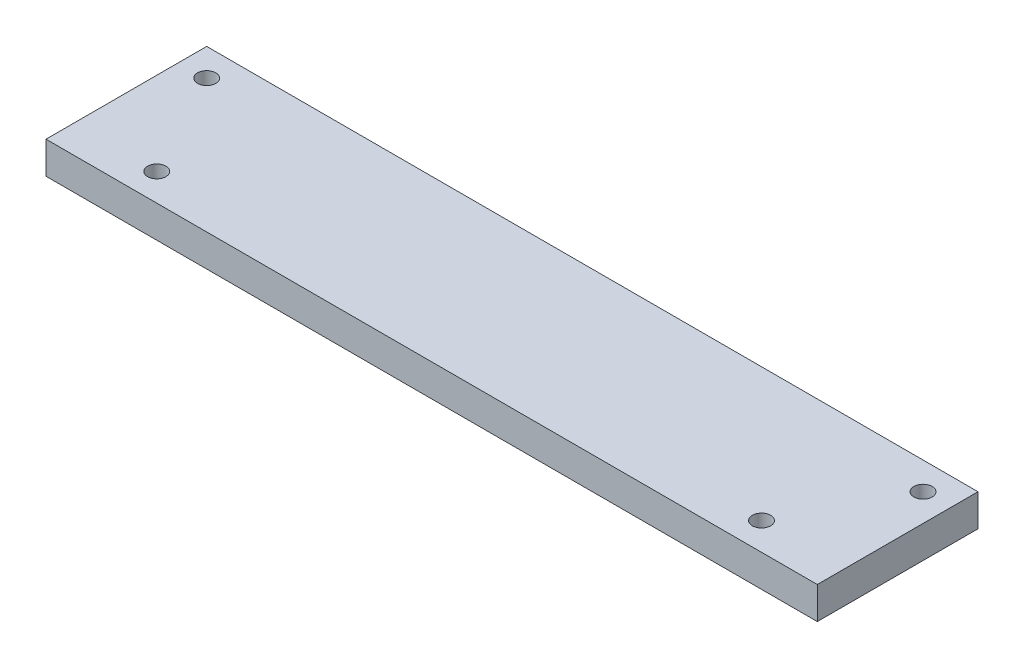
SolidWorks part; units mm, degrees
material "Pine"
ref_plane "Front Plane" through (0, 0, 0) normal (0, 0, 1) x (1, 0, 0)
ref_plane "Top Plane" through (0, 0, 0) normal (0, 1, 0) x (1, 0, 0)
ref_plane "Right Plane" through (0, 0, 0) normal (1, 0, 0) x (0, 0, -1)
sketch "Sketch2" plane through (0, 0, 0) normal (0, 1, 0) x (1, 0, 0)
  line L0 (293.9415, 52.6415) -> (271.8921, 10.8585) construction
  line L1 (0, 0) -> (304.8, 0)
  line L2 (0, 0) -> (0, 63.5)
  line L3 (0, 63.5) -> (304.8, 63.5)
  line L4 (304.8, 0) -> (304.8, 63.5)
  line L5 (152.4, 63.5) -> (152.4, -83.5762) construction
  circle A0 centre (293.9415, 52.6415) radius 3.6195
  circle A1 centre (271.8921, 10.8585) radius 3.6195
  circle A2 centre (32.9079, 10.8585) radius 3.6195
  circle A3 centre (10.8585, 52.6415) radius 3.6195
  point P11 (152.4, 63.5)
  dimension "D3" = 7.239
  dimension "D1" = 304.8
  dimension "D2" = 63.5
  dimension "D4" = 47.244
  dimension "D5" = 10.8585
  dimension "D6" = 10.8585
  dimension "D7" = 10.8585
extrude "Boss-Extrude1" add sketch "Sketch2" along normal blind 12.7
equation "\"D5@Sketch2\"=1.5*\"D3@Sketch2\""
equation "\"D7@Sketch2\"=\"D5@Sketch2\""
equation "\"D6@Sketch2\"=\"D5@Sketch2\""
